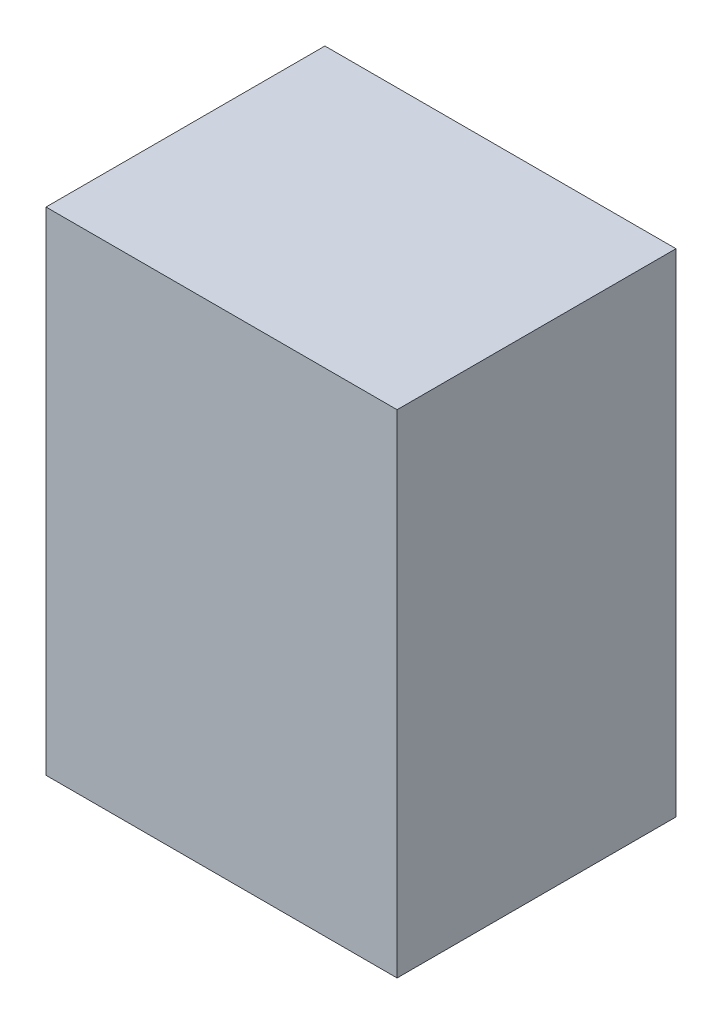
SolidWorks part; units mm, degrees
ref_plane "Front Plane" through (0, 0, 0) normal (0, 0, 1) x (1, 0, 0)
ref_plane "Top Plane" through (0, 0, 0) normal (0, 1, 0) x (1, 0, 0)
ref_plane "Right Plane" through (0, 0, 0) normal (1, 0, 0) x (0, 0, -1)
sketch "Sketch1" plane through (0, 0, 0) normal (0, 0, 1) x (1, 0, 0)
  line L1 (0, 0) -> (107, 0)
  line L2 (0, 0) -> (0, 150)
  line L3 (0, 150) -> (107, 150)
  line L4 (107, 0) -> (107, 150)
  dimension "D1" = 107
  dimension "D2" = 150
extrude "Boss-Extrude1" add sketch "Sketch1" along normal blind 85
